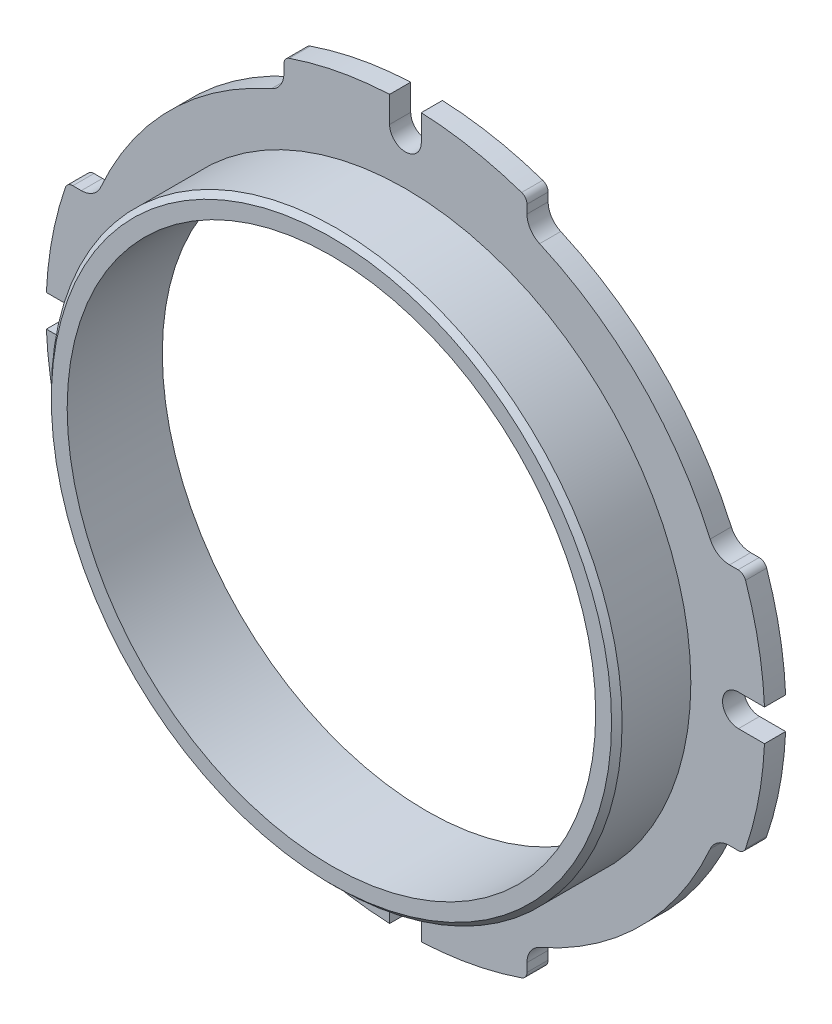
SolidWorks part; units mm, degrees
ref_plane "Front Plane" through (0, 0, 0) normal (0, 0, 1) x (1, 0, 0)
ref_plane "Top Plane" through (0, 0, 0) normal (0, 1, 0) x (1, 0, 0)
ref_plane "Right Plane" through (0, 0, 0) normal (1, 0, 0) x (0, 0, -1)
sketch "Sketch1" plane through (0, 0, 0) normal (0, 0, 1) x (1, 0, 0)
  line L0 (-11.5, 30.6594) -> (-11.5, 31.4643)
  line L1 (-11.5, 11.5) -> (11.5, 11.5) construction
  line L2 (-11.5, 11.5) -> (-11.5, -11.5) construction
  line L3 (-11.5, -11.5) -> (11.5, -11.5) construction
  line L4 (11.5, 11.5) -> (11.5, -11.5) construction
  line L5 (-11.5, 11.5) -> (11.5, -11.5) construction
  line L6 (-11.5, -11.5) -> (11.5, 11.5) construction
  line L7 (11.5, 31.4643) -> (11.5, 30.6594)
  line L8 (30.6594, 11.5) -> (31.4643, 11.5)
  line L9 (30.6594, -11.5) -> (31.4643, -11.5)
  line L10 (11.5, -30.6594) -> (11.5, -31.4643)
  line L11 (-11.5, -31.4643) -> (-11.5, -30.6594)
  line L12 (-30.6594, -11.5) -> (-31.4643, -11.5)
  line L13 (-31.4643, 11.5) -> (-30.6594, 11.5)
  circle A0 centre (0, 0) radius 31.5 construction
  circle A1 centre (0, 0) radius 27 construction
  circle A2 centre (0, 0) radius 25
  circle A3 centre (0, 0) radius 34 construction
  arc A4 (32.174, 10.9925) -> (32.174, -10.9925) centre (0, 0) cw
  arc A5 (10.9925, 32.174) -> (-10.9925, 32.174) centre (0, 0) ccw
  arc A6 (-32.174, 10.9925) -> (-32.174, -10.9925) centre (0, 0) ccw
  arc A7 (-10.9925, -32.174) -> (10.9925, -32.174) centre (0, 0) ccw
  arc A8 (-12.694, 28.829) -> (-28.829, 12.694) centre (0, 0) ccw
  arc A9 (28.829, 12.694) -> (12.694, 28.829) centre (0, 0) ccw
  arc A10 (12.694, -28.829) -> (28.829, -12.694) centre (0, 0) ccw
  arc A11 (-28.829, -12.694) -> (-12.694, -28.829) centre (0, 0) ccw
  arc A12 (-12.694, 28.829) -> (-11.5, 30.6594) centre (-13.5, 30.6594) ccw
  arc A13 (12.694, 28.829) -> (11.5, 30.6594) centre (13.5, 30.6594) cw
  arc A14 (28.829, 12.694) -> (30.6594, 11.5) centre (30.6594, 13.5) ccw
  arc A15 (28.829, -12.694) -> (30.6594, -11.5) centre (30.6594, -13.5) cw
  arc A16 (12.694, -28.829) -> (11.5, -30.6594) centre (13.5, -30.6594) ccw
  arc A17 (-12.694, -28.829) -> (-11.5, -30.6594) centre (-13.5, -30.6594) cw
  arc A18 (-28.829, -12.694) -> (-30.6594, -11.5) centre (-30.6594, -13.5) ccw
  arc A19 (-28.829, 12.694) -> (-30.6594, 11.5) centre (-30.6594, 13.5) cw
  arc A20 (-32.174, -10.9925) -> (-31.4643, -11.5) centre (-31.4643, -10.75) ccw
  arc A21 (-10.9925, -32.174) -> (-11.5, -31.4643) centre (-10.75, -31.4643) cw
  arc A22 (10.9925, -32.174) -> (11.5, -31.4643) centre (10.75, -31.4643) ccw
  arc A23 (32.174, -10.9925) -> (31.4643, -11.5) centre (31.4643, -10.75) cw
  arc A24 (32.174, 10.9925) -> (31.4643, 11.5) centre (31.4643, 10.75) ccw
  arc A25 (10.9925, 32.174) -> (11.5, 31.4643) centre (10.75, 31.4643) cw
  arc A26 (-10.9925, 32.174) -> (-11.5, 31.4643) centre (-10.75, 31.4643) ccw
  arc A27 (-32.174, 10.9925) -> (-31.4643, 11.5) centre (-31.4643, 10.75) cw
  point P28 (-11.5, 29.3258)
  point P33 (29.3258, 11.5)
  point P36 (29.3258, -11.5)
  point P39 (11.5, -29.3258)
  point P44 (-29.3258, -11.5)
  point P47 (-29.3258, 11.5)
  point P50 (-31.9961, -11.5)
  point P53 (-11.5, -31.9961)
  point P56 (11.5, -31.9961)
  point P59 (31.9961, -11.5)
  point P62 (31.9961, 11.5)
  point P65 (11.5, 31.9961)
  point P68 (-11.5, 31.9961)
  point P71 (-31.9961, 11.5)
  dimension "D1" = 2
  dimension "D2" = 0.75
extrude "Boss-Extrude1" add sketch "Sketch1" along normal blind 2
sketch "Sketch2" plane through (0, 0, 2) normal (0, 0, 1) x (1, 0, 0)
  circle A0 centre (0, 0) radius 27
  circle A1 centre (0, 0) radius 25
extrude "Boss-Extrude2" add sketch "Sketch2" along normal blind 7
sketch "Sketch3" plane through (0, 0, 2) normal (0, 0, 1) x (1, 0, 0)
  line L0 (31.5, 1.5) -> (35.3275, 1.5)
  line L1 (35.3275, 1.5) -> (35.3275, -1.5)
  line L2 (35.3275, -1.5) -> (31.5, -1.5)
  line L3 (-1.5, -31.5) -> (-1.5, -34.386)
  line L4 (-1.5, -34.386) -> (1.5, -34.386)
  line L5 (1.5, -34.386) -> (1.5, -31.5)
  line L6 (-31.5, -1.5) -> (-36.6408, -1.5)
  line L7 (-36.6408, -1.5) -> (-36.6408, 1.5)
  line L8 (-36.6408, 1.5) -> (-31.5, 1.5)
  line L9 (-1.5, 31.5) -> (-1.5, 35.3013)
  line L10 (-1.5, 35.3013) -> (1.5, 35.3013)
  line L11 (1.5, 35.3013) -> (1.5, 31.5)
  circle A0 centre (0, 0) radius 31.5 construction
  circle A1 centre (-31.5, 0) radius 1.5 construction
  circle A2 centre (31.5, 0) radius 1.5 construction
  circle A3 centre (0, 31.5) radius 1.5 construction
  circle A4 centre (0, -31.5) radius 1.5 construction
  arc A5 (1.5, 31.5) -> (-1.5, 31.5) centre (0, 31.5) cw
  arc A6 (-31.5, 1.5) -> (-31.5, -1.5) centre (-31.5, 0) cw
  arc A7 (-1.5, -31.5) -> (1.5, -31.5) centre (0, -31.5) cw
  arc A8 (31.5, -1.5) -> (31.5, 1.5) centre (31.5, 0) cw
extrude "Cut-Extrude1" cut sketch "Sketch3" against normal through all
chamfer "Chamfer1" distance 0.5 angle 45 1 edges at (27, 0, 9)
